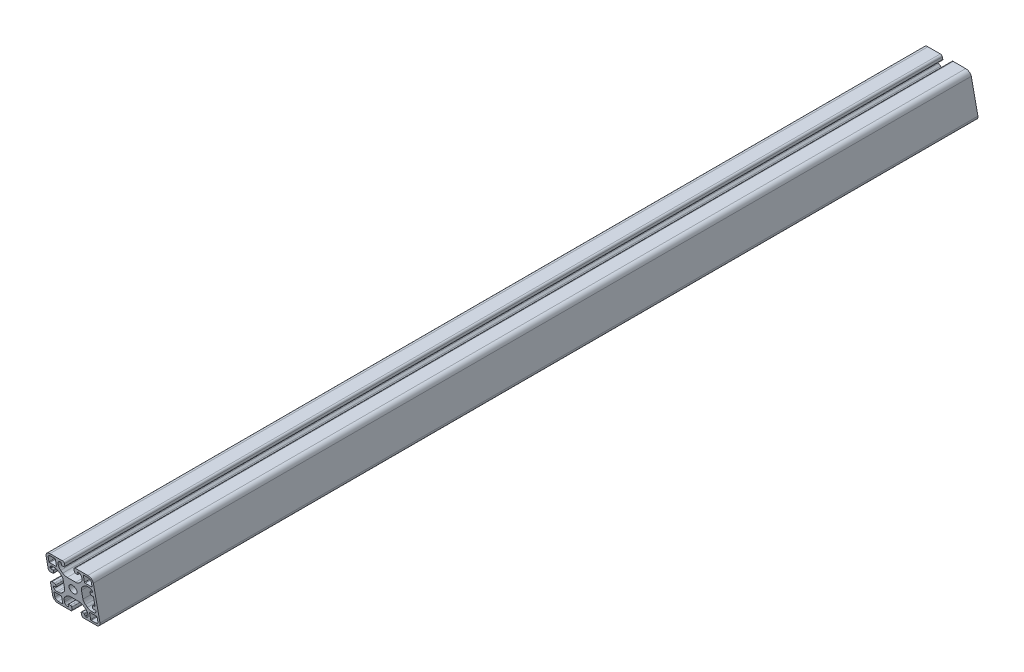
SolidWorks part; units mm, degrees
ref_plane "Piano frontale" through (0, 0, 0) normal (0, 0, 1) x (1, 0, 0)
ref_plane "Piano superiore" through (0, 0, 0) normal (0, 1, 0) x (1, 0, 0)
ref_plane "Piano destro" through (0, 0, 0) normal (1, 0, 0) x (0, 0, -1)
ref_plane "Piano1" through (0, 0, -340) normal (0, 0, -1) x (-1, 0, 0)
sketch "Schizzo1" plane through (0, 0, -340) normal (0, 0, -1) x (-1, 0, 0)
  line L0 (-12.3, -18.2) -> (-16, -18.2)
  line L1 (-18.2, -16) -> (-18.2, -12.3)
  line L2 (-17.7, -11.8) -> (-12.3, -11.8)
  line L3 (-11.8, -12.3) -> (-11.8, -17.7)
  line L4 (-11.8, 17.7) -> (-11.8, 12.3)
  line L5 (-12.3, 11.8) -> (-17.7, 11.8)
  line L6 (-18.2, 12.3) -> (-18.2, 16)
  line L7 (-16, 18.2) -> (-12.3, 18.2)
  line L8 (18.2, 16) -> (18.2, 12.3)
  line L9 (17.7, 11.8) -> (12.3, 11.8)
  line L10 (11.8, 12.3) -> (11.8, 17.7)
  line L11 (12.3, 18.2) -> (16, 18.2)
  line L12 (6.5, -15.5) -> (5, -15.5)
  line L13 (4, -16.5) -> (4, -18.5)
  line L14 (5.5, -20) -> (16, -20)
  line L15 (20, -16) -> (20, -5.5)
  line L16 (18.5, -4) -> (16.5, -4)
  line L17 (15.5, -5) -> (15.5, -6.5)
  line L18 (16, -7) -> (17.55, -7)
  line L19 (18, -7.45) -> (18, -7.5)
  line L20 (15.5, -10) -> (14.1924, -10)
  line L21 (10.6569, -8.5355) -> (9.2145, -7.0931)
  line L22 (7.75, -3.5576) -> (7.75, 3.5576)
  line L23 (9.2145, 7.0931) -> (10.6569, 8.5355)
  line L24 (14.1924, 10) -> (15.5, 10)
  line L25 (18, 7.5) -> (18, 7.45)
  line L26 (17.55, 7) -> (16, 7)
  line L27 (15.5, 6.5) -> (15.5, 5)
  line L28 (16.5, 4) -> (18.5, 4)
  line L29 (20, 5.5) -> (20, 16)
  line L30 (16, 20) -> (5.5, 20)
  line L31 (4, 18.5) -> (4, 16.5)
  line L32 (5, 15.5) -> (6.5, 15.5)
  line L33 (7, 16) -> (7, 17.55)
  line L34 (7.45, 18) -> (7.5, 18)
  line L35 (10, 15.5) -> (10, 14.1924)
  line L36 (8.5355, 10.6569) -> (7.0931, 9.2145)
  line L37 (3.5576, 7.75) -> (-3.5576, 7.75)
  line L38 (-7.0931, 9.2145) -> (-8.5355, 10.6569)
  line L39 (-10, 14.1924) -> (-10, 15.5)
  line L40 (-7.5, 18) -> (-7.45, 18)
  line L41 (-7, 17.55) -> (-7, 16)
  line L42 (-6.5, 15.5) -> (-5, 15.5)
  line L43 (-4, 16.5) -> (-4, 18.5)
  line L44 (-5.5, 20) -> (-16, 20)
  line L45 (-20, 16) -> (-20, -16)
  line L46 (-16, -20) -> (-5.5, -20)
  line L47 (-4, -18.5) -> (-4, -16.5)
  line L48 (-5, -15.5) -> (-6.5, -15.5)
  line L49 (-7, -16) -> (-7, -17.55)
  line L50 (-7.45, -18) -> (-7.5, -18)
  line L51 (-10, -15.5) -> (-10, -14.1924)
  line L52 (-8.5355, -10.6569) -> (-7.0931, -9.2145)
  line L53 (-3.5576, -7.75) -> (3.5576, -7.75)
  line L54 (7.0931, -9.2145) -> (8.5355, -10.6569)
  line L55 (10, -14.1924) -> (10, -15.5)
  line L56 (7.5, -18) -> (7.45, -18)
  line L57 (7, -17.55) -> (7, -16)
  line L58 (18.2, -12.3) -> (18.2, -16)
  line L59 (16, -18.2) -> (12.3, -18.2)
  line L60 (11.8, -17.7) -> (11.8, -12.3)
  line L61 (12.3, -11.8) -> (17.7, -11.8)
  line L62 (-16, 7) -> (-17.5, 7)
  line L63 (-15.5, 10) -> (-14.1924, 10)
  line L64 (-10.6569, 8.5355) -> (-9.2145, 7.0931)
  line L65 (-7.75, 3.5576) -> (-7.75, -3.5576)
  line L66 (-9.2145, -7.0931) -> (-10.6569, -8.5355)
  line L67 (-14.1924, -10) -> (-15.5, -10)
  line L68 (-17.5, -7) -> (-16, -7)
  line L69 (-15.5, -6.5) -> (-15.5, -5)
  line L70 (-16.5, -4) -> (-17.5, -4)
  line L71 (-18, -3.5) -> (-18, 3.5)
  line L72 (-17.5, 4) -> (-16.5, 4)
  line L73 (-15.5, 5) -> (-15.5, 6.5)
  arc A0 (-16, -18.2) -> (-18.2, -16) centre (-16, -16) cw
  arc A1 (-18.2, -12.3) -> (-17.7, -11.8) centre (-17.7, -12.3) cw
  arc A2 (-12.3, -11.8) -> (-11.8, -12.3) centre (-12.3, -12.3) cw
  arc A3 (-11.8, -17.7) -> (-12.3, -18.2) centre (-12.3, -17.7) cw
  arc A4 (-12.3, 18.2) -> (-11.8, 17.7) centre (-12.3, 17.7) cw
  arc A5 (-11.8, 12.3) -> (-12.3, 11.8) centre (-12.3, 12.3) cw
  arc A6 (-17.7, 11.8) -> (-18.2, 12.3) centre (-17.7, 12.3) cw
  arc A7 (-18.2, 16) -> (-16, 18.2) centre (-16, 16) cw
  arc A8 (16, 18.2) -> (18.2, 16) centre (16, 16) cw
  arc A9 (18.2, 12.3) -> (17.7, 11.8) centre (17.7, 12.3) cw
  arc A10 (12.3, 11.8) -> (11.8, 12.3) centre (12.3, 12.3) cw
  arc A11 (11.8, 17.7) -> (12.3, 18.2) centre (12.3, 17.7) cw
  arc A12 (5, -15.5) -> (4, -16.5) centre (5, -16.5) ccw
  arc A13 (4, -18.5) -> (5.5, -20) centre (5.5, -18.5) ccw
  arc A14 (16, -20) -> (20, -16) centre (16, -16) ccw
  arc A15 (20, -5.5) -> (18.5, -4) centre (18.5, -5.5) ccw
  arc A16 (16.5, -4) -> (15.5, -5) centre (16.5, -5) ccw
  arc A17 (15.5, -6.5) -> (16, -7) centre (16, -6.5) ccw
  arc A18 (17.55, -7) -> (18, -7.45) centre (17.55, -7.45) cw
  arc A19 (18, -7.5) -> (15.5, -10) centre (15.5, -7.5) cw
  arc A20 (14.1924, -10) -> (10.6569, -8.5355) centre (14.1924, -5) cw
  arc A21 (9.2145, -7.0931) -> (7.75, -3.5576) centre (12.75, -3.5576) cw
  arc A22 (7.75, 3.5576) -> (9.2145, 7.0931) centre (12.75, 3.5576) cw
  arc A23 (10.6569, 8.5355) -> (14.1924, 10) centre (14.1924, 5) cw
  arc A24 (15.5, 10) -> (18, 7.5) centre (15.5, 7.5) cw
  arc A25 (18, 7.45) -> (17.55, 7) centre (17.55, 7.45) cw
  arc A26 (16, 7) -> (15.5, 6.5) centre (16, 6.5) ccw
  arc A27 (15.5, 5) -> (16.5, 4) centre (16.5, 5) ccw
  arc A28 (18.5, 4) -> (20, 5.5) centre (18.5, 5.5) ccw
  arc A29 (20, 16) -> (16, 20) centre (16, 16) ccw
  arc A30 (5.5, 20) -> (4, 18.5) centre (5.5, 18.5) ccw
  arc A31 (4, 16.5) -> (5, 15.5) centre (5, 16.5) ccw
  arc A32 (6.5, 15.5) -> (7, 16) centre (6.5, 16) ccw
  arc A33 (7, 17.55) -> (7.45, 18) centre (7.45, 17.55) cw
  arc A34 (7.5, 18) -> (10, 15.5) centre (7.5, 15.5) cw
  arc A35 (10, 14.1924) -> (8.5355, 10.6569) centre (5, 14.1924) cw
  arc A36 (7.0931, 9.2145) -> (3.5576, 7.75) centre (3.5576, 12.75) cw
  arc A37 (-3.5576, 7.75) -> (-7.0931, 9.2145) centre (-3.5576, 12.75) cw
  arc A38 (-8.5355, 10.6569) -> (-10, 14.1924) centre (-5, 14.1924) cw
  arc A39 (-10, 15.5) -> (-7.5, 18) centre (-7.5, 15.5) cw
  arc A40 (-7.45, 18) -> (-7, 17.55) centre (-7.45, 17.55) cw
  arc A41 (-7, 16) -> (-6.5, 15.5) centre (-6.5, 16) ccw
  arc A42 (-5, 15.5) -> (-4, 16.5) centre (-5, 16.5) ccw
  arc A43 (-4, 18.5) -> (-5.5, 20) centre (-5.5, 18.5) ccw
  arc A44 (-16, 20) -> (-20, 16) centre (-16, 16) ccw
  arc A45 (-20, -16) -> (-16, -20) centre (-16, -16) ccw
  arc A46 (-5.5, -20) -> (-4, -18.5) centre (-5.5, -18.5) ccw
  arc A47 (-4, -16.5) -> (-5, -15.5) centre (-5, -16.5) ccw
  arc A48 (-6.5, -15.5) -> (-7, -16) centre (-6.5, -16) ccw
  arc A49 (-7, -17.55) -> (-7.45, -18) centre (-7.45, -17.55) cw
  arc A50 (-7.5, -18) -> (-10, -15.5) centre (-7.5, -15.5) cw
  arc A51 (-10, -14.1924) -> (-8.5355, -10.6569) centre (-5, -14.1924) cw
  arc A52 (-7.0931, -9.2145) -> (-3.5576, -7.75) centre (-3.5576, -12.75) cw
  arc A53 (3.5576, -7.75) -> (7.0931, -9.2145) centre (3.5576, -12.75) cw
  arc A54 (8.5355, -10.6569) -> (10, -14.1924) centre (5, -14.1924) cw
  arc A55 (10, -15.5) -> (7.5, -18) centre (7.5, -15.5) cw
  arc A56 (7.45, -18) -> (7, -17.55) centre (7.45, -17.55) cw
  arc A57 (7, -16) -> (6.5, -15.5) centre (6.5, -16) ccw
  arc A58 (17.7, -11.8) -> (18.2, -12.3) centre (17.7, -12.3) cw
  arc A59 (18.2, -16) -> (16, -18.2) centre (16, -16) cw
  arc A60 (12.3, -18.2) -> (11.8, -17.7) centre (12.3, -17.7) cw
  arc A61 (11.8, -12.3) -> (12.3, -11.8) centre (12.3, -12.3) cw
  circle A62 centre (0, 0) radius 3.4
  arc A63 (-15.5, 6.5) -> (-16, 7) centre (-16, 6.5) ccw
  arc A64 (-17.5, 7) -> (-18, 7.5) centre (-17.5, 7.5) cw
  arc A65 (-18, 7.5) -> (-15.5, 10) centre (-15.5, 7.5) cw
  arc A66 (-14.1924, 10) -> (-10.6569, 8.5355) centre (-14.1924, 5) cw
  arc A67 (-9.2145, 7.0931) -> (-7.75, 3.5576) centre (-12.75, 3.5576) cw
  arc A68 (-7.75, -3.5576) -> (-9.2145, -7.0931) centre (-12.75, -3.5576) cw
  arc A69 (-10.6569, -8.5355) -> (-14.1924, -10) centre (-14.1924, -5) cw
  arc A70 (-15.5, -10) -> (-18, -7.5) centre (-15.5, -7.5) cw
  arc A71 (-18, -7.5) -> (-17.5, -7) centre (-17.5, -7.5) cw
  arc A72 (-16, -7) -> (-15.5, -6.5) centre (-16, -6.5) ccw
  arc A73 (-15.5, -5) -> (-16.5, -4) centre (-16.5, -5) ccw
  arc A74 (-17.5, -4) -> (-18, -3.5) centre (-17.5, -3.5) cw
  arc A75 (-18, 3.5) -> (-17.5, 4) centre (-17.5, 3.5) cw
  arc A76 (-16.5, 4) -> (-15.5, 5) centre (-16.5, 5) ccw
extrude "Estrusione-Estrusione1" add sketch "Schizzo1" against normal blind 750
sketch "Schizzo9" plane through (20, 0, 0) normal (1, 0, 0) x (0, 0, -1)
  line L0 (340, -16) -> (340, 16) construction
  line L1 (-410, 16) -> (-410, -16) construction
  line L2 (340, 16) -> (340, 20) construction
  line L3 (340, 20) -> (-410, 20) construction
  line L4 (-410, 20) -> (-410, 16) construction
  line L5 (340, -20) -> (340, -16) construction
  line L6 (-410, -16) -> (-410, -20) construction
  line L7 (-410, -20) -> (340, -20) construction
  line L8 (340, -16) -> (340, 16)
  line L9 (-410, 16) -> (-410, -16)
  line L10 (340, 16) -> (340, 20)
  line L11 (340, 20) -> (-410, 20)
  line L12 (-410, 20) -> (-410, 16)
  line L13 (340, -20) -> (340, -16)
  line L14 (-410, -16) -> (-410, -20)
  line L15 (-410, -20) -> (340, -20)
  line L16 (-410, 20) -> (-402.9522, -20)
  line L18 (316.8895, -20) -> (316.8895, 20)
  line L19 (340, -20) -> (332.9469, 20)
extrude "Taglio-Estrusione1" cut sketch "Schizzo9" against normal through all
